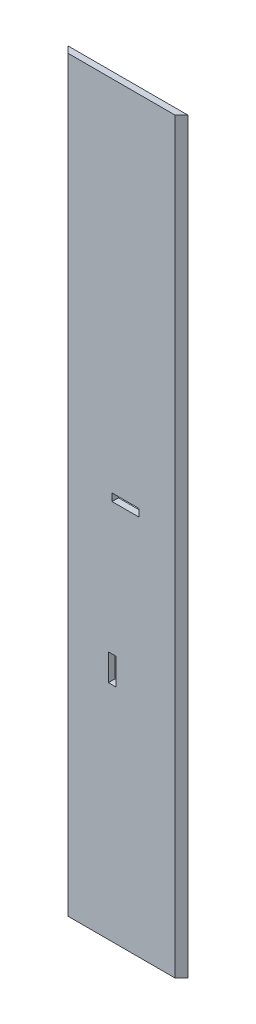
SolidWorks part; units mm, degrees
material "Balsa"
ref_plane "Front Plane" through (0, 0, 0) normal (1, 0, 0) x (0, 1, 0)
ref_plane "Top Plane" through (0, 0, 0) normal (0, 0, 1) x (0, 1, 0)
ref_plane "Right Plane" through (0, 0, 0) normal (0, 1, 0) x (-1, 0, 0)
sketch "Sketch1" plane through (0, 0, 0) normal (0, 0, 1) x (0, 1, 0)
  line L1 (-175, -25) -> (175, -25)
  line L2 (-175, -25) -> (-175, 25)
  line L3 (-175, 25) -> (175, 25)
  line L4 (175, -25) -> (175, 25)
  line L5 (-175, -25) -> (175, 25) construction
  line L6 (-175, 25) -> (175, -25) construction
  point P0 (0, 0)
  dimension "D1" = 50
  dimension "D2" = 350
extrude "Boss-Extrude1" add sketch "Sketch1" along normal blind 3
sketch "Sketch2" plane through (0, -175, 0) normal (0, -1, 0) x (1, 0, 0)
  line L0 (-25, 3) -> (-25, 0)
  line L1 (-25, 0) -> (-28, 0)
  line L2 (-25, 3) -> (-28, 0)
  line L3 (0, 0) -> (0, 3) construction
  line L4 (-25, 3) -> (25, 3) construction
  line L5 (25, 3) -> (28, 0)
  line L6 (25, 0) -> (28, 0)
  line L7 (25, 3) -> (25, 0)
  dimension "D1" = 45
extrude "Boss-Extrude2" add sketch "Sketch2" against normal through all
sketch "Sketch3" plane through (0, 0, 0) normal (0, 0, -1) x (1, 0, 0)
  line L4 (-28, -175) -> (28, -175)
  line L5 (28, -175) -> (28, 175)
  line L6 (28, 175) -> (-28, 175)
  line L7 (-28, 175) -> (-28, -175)
  line L8 (-28, -175) -> (28, -175)
  line L9 (28, -175) -> (28, 175)
  line L10 (28, 175) -> (-28, 175)
  line L11 (-28, 175) -> (-28, -175)
  line L16 (-6.1908, 58.3074) -> (-2.6908, 58.3074)
  line L17 (-2.6908, 70.8074) -> (-2.6908, 58.3074)
  line L18 (-6.1908, 70.8074) -> (-2.6908, 70.8074)
  line L19 (-6.1908, 70.8074) -> (-6.1908, 58.3074)
  line L20 (8.0381, -3.5) -> (8.0381, -7)
  line L21 (-4.4619, -7) -> (8.0381, -7)
  line L22 (-4.4619, -3.5) -> (-4.4619, -7)
  line L23 (-4.4619, -3.5) -> (8.0381, -3.5)
  dimension "D1" = 0
extrude "Cut-Extrude2" cut sketch "Sketch3" against normal through all flip side to cut
